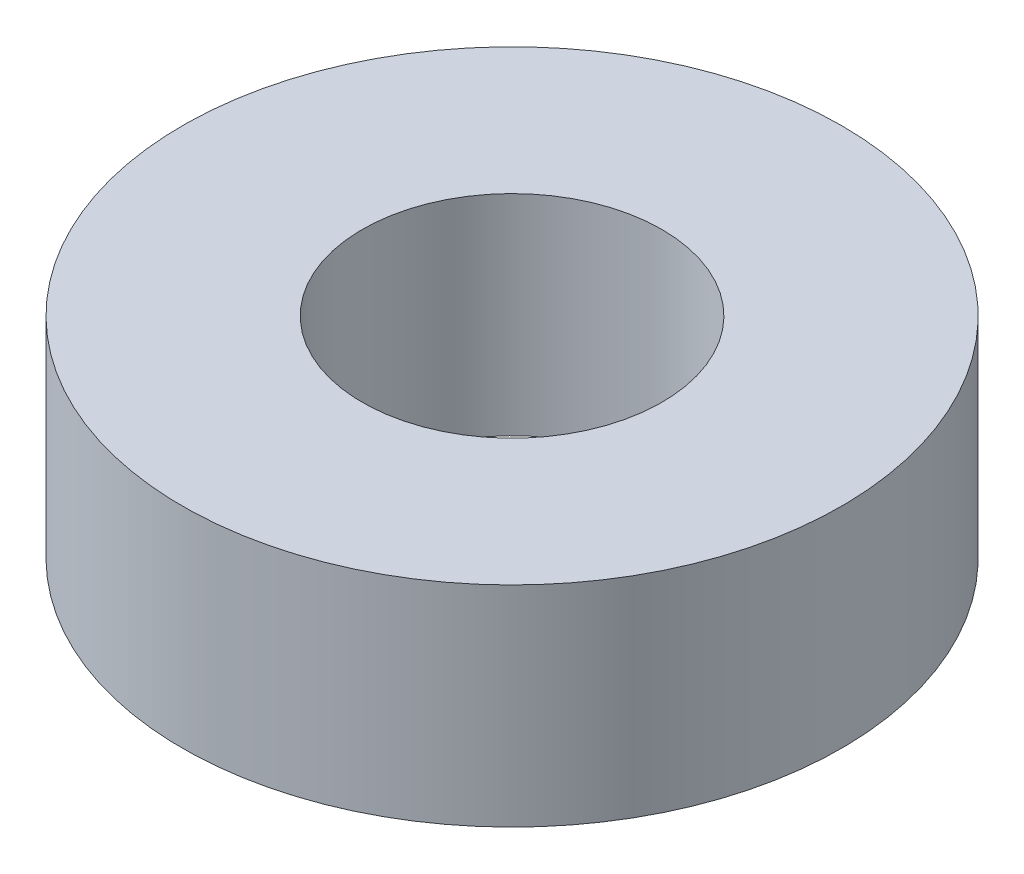
SolidWorks part; units mm, degrees
material "PTFE (general)"
ref_plane "Front Plane" through (0, 0, 0) normal (0, 0, 1) x (1, 0, 0)
ref_plane "Top Plane" through (0, 0, 0) normal (0, 1, 0) x (1, 0, 0)
ref_plane "Right Plane" through (0, 0, 0) normal (1, 0, 0) x (0, 0, -1)
sketch "Sketch1" plane through (0, 0, 0) normal (0, 0, 1) x (1, 0, 0)
  line L0 (0, 0) -> (0, 12.3934) construction
  line L1 (5, 0) -> (11, 0)
  line L2 (5, 0) -> (5, 7)
  line L3 (5, 7) -> (11, 7)
  line L4 (11, 0) -> (11, 7)
  dimension "D1" = 10
  dimension "D2" = 22
  dimension "D3" = 7
revolve "Revolve1" add sketch "Sketch1" angle 360 about L0
